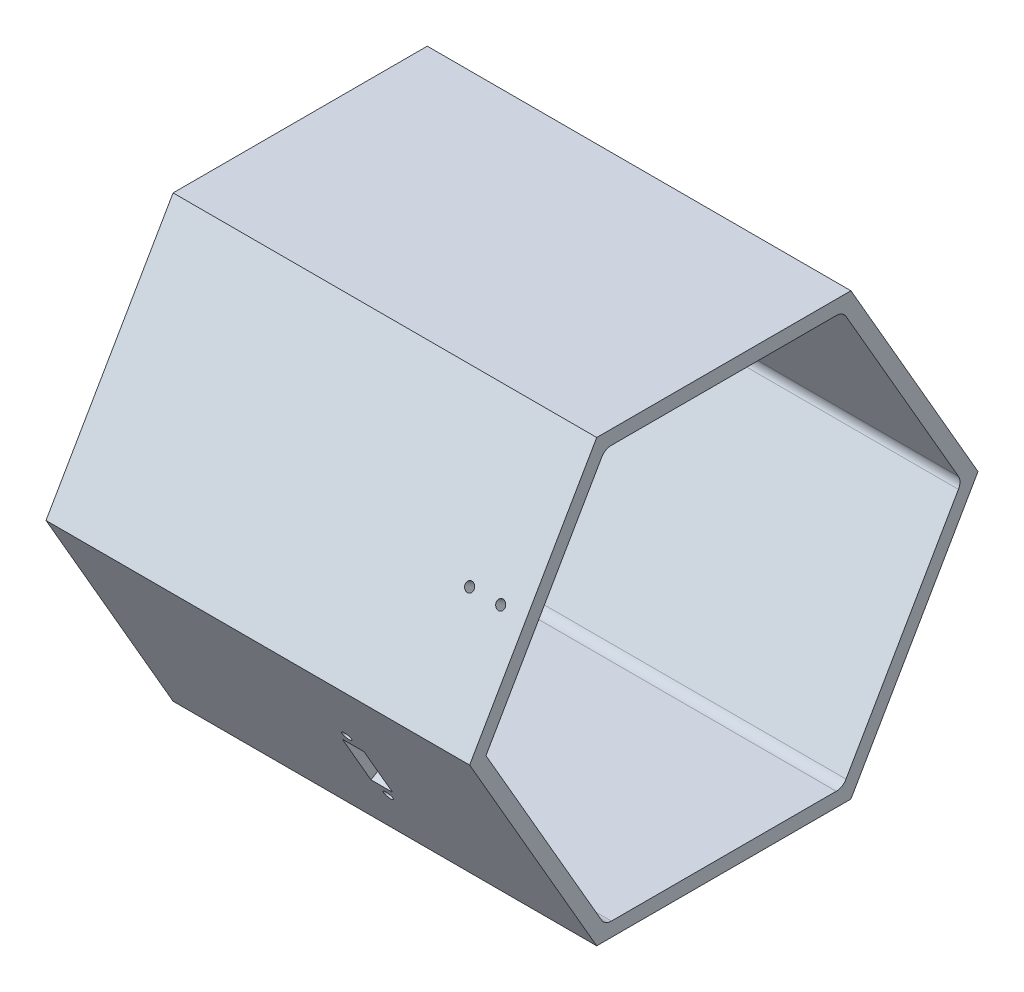
SolidWorks part; units mm, degrees
other "Markup1"
sketch "Sketch8"
ref_plane "Front Plane" through (0, 0, 0) normal (0, 0, 1) x (1, 0, 0)
ref_plane "Top Plane" through (0, 0, 0) normal (0, 1, 0) x (1, 0, 0)
ref_plane "Right Plane" through (0, 0, 0) normal (1, 0, 0) x (0, 0, -1)
sketch "Sketch1" plane through (0, 0, 0) normal (1, 0, 0) x (0, 0, -1)
  line L1 (90, 0) -> (45, 77.9423)
  line L2 (45, 77.9423) -> (-45, 77.9423)
  line L3 (-45, 77.9423) -> (-90, 0)
  line L4 (-90, 0) -> (-45, -77.9423)
  line L5 (-45, -77.9423) -> (45, -77.9423)
  line L6 (45, -77.9423) -> (90, 0)
  circle A0 centre (0, 0) radius 77.9423 construction
  dimension "D1" = 180
extrude "Boss-Extrude1" add sketch "Sketch1" along normal blind 200
sketch "Sketch2" plane through (200, 0, 0) normal (1, 0, 0) x (0, 0, -1)
  line L0 (-45, 77.9423) -> (-90, 0) construction
  line L1 (84.2265, 0) -> (42.1132, 72.9423)
  line L2 (42.1132, 72.9423) -> (-42.1132, 72.9423)
  line L3 (-42.1132, 72.9423) -> (-84.2265, 0)
  line L4 (-84.2265, 0) -> (-42.1132, -72.9423)
  line L5 (-42.1132, -72.9423) -> (42.1132, -72.9423)
  line L6 (42.1132, -72.9423) -> (84.2265, 0)
  circle A0 centre (0, 0) radius 72.9423 construction
  dimension "D1" = 5
extrude "Cut-Extrude1" cut sketch "Sketch2" against normal blind 195
sketch "Sketch5" plane through (0, -38.9711, 67.5) normal (0, -0.5, 0.866) x (1, 0, 0)
  line L0 (20, 45) -> (20, -45) construction
  line L1 (200, 45) -> (0, 45) construction
  line L2 (200, -45) -> (0, -45) construction
  line L3 (65, 45) -> (65, -45) construction
  line L4 (0, 45) -> (0, -45) construction
  line L5 (73.65, -5) -> (64, -5) construction
  line L6 (65, 5.1) -> (72.65, 5.1)
  line L7 (65, 5.1) -> (65, -15.1)
  line L8 (65, -15.1) -> (72.65, -15.1)
  line L9 (72.65, 5.1) -> (72.65, -15.1)
  line L10 (65, 5.1) -> (72.65, -15.1) construction
  line L11 (65, -15.1) -> (72.65, 5.1) construction
  line L12 (64, -15.5) -> (73.65, -15.5) construction
  line L13 (64, -15.5) -> (64, 5.5) construction
  line L14 (64, 5.5) -> (73.65, 5.5) construction
  line L15 (73.65, -15.5) -> (73.65, 5.5) construction
  line L16 (68.825, 14) -> (68.825, 5.5) construction
  line L17 (72.575, 9.75) -> (65.075, 9.75) construction
  line L18 (66.95, 6.5024) -> (70.7, 6.5024) construction
  line L19 (70.7, 6.5024) -> (72.575, 9.75) construction
  line L20 (72.575, 9.75) -> (70.7, 12.9976) construction
  line L21 (70.7, 12.9976) -> (66.95, 12.9976) construction
  line L22 (66.95, 12.9976) -> (65.075, 9.75) construction
  line L23 (65.075, 9.75) -> (66.95, 6.5024) construction
  arc A2 (73.65, 5.5) -> (64, 5.5) centre (68.825, 8.3806) ccw construction
  circle A3 centre (68.825, 9.75) radius 3.2476 construction
  circle A4 centre (68.825, 9.75) radius 1.65
  circle A6 centre (68.825, -19.75) radius 1.65
  point P14 (68.825, -5)
  point P15 (68.825, -5)
  dimension "D11" = 8.5
  dimension "D12" = 3.3
  dimension "D1" = 20
  dimension "D2" = 65
  dimension "D3" = 39.9
  dimension "D4" = 20.2
  dimension "D5" = 7.65
  dimension "D6" = 29.9
  dimension "D7" = 9.65
  dimension "D8" = 21
  dimension "D9" = 1
  dimension "D10" = 0.4
extrude "Cut-Extrude4" cut sketch "Sketch5" against normal blind 70
sketch "Sketch7" plane through (5, 0, 0) normal (1, 0, 0) x (0, 0, -1)
  line L0 (42.1132, 72.9423) -> (-42.1132, -72.9423) construction
  line L1 (-42.1132, 72.9423) -> (42.1132, -72.9423) construction
  line L2 (84.2265, 0) -> (-84.2265, 0) construction
  circle A0 centre (0, 0) radius 4.5
  circle A1 centre (60, 0) radius 3
  circle A2 centre (30, 51.9615) radius 3
  circle A3 centre (-30, 51.9615) radius 3
  circle A4 centre (-60, 0) radius 3
  circle A5 centre (-30, -51.9615) radius 3
  circle A6 centre (30, -51.9615) radius 3
  dimension "D1" = 9
  dimension "D2" = 6
  dimension "D3" = 6
  dimension "D4" = 6
  dimension "D5" = 6
  dimension "D6" = 6
  dimension "D7" = 6
  dimension "D8" = 60
  dimension "D9" = 60
  dimension "D10" = 60
  dimension "D11" = 60
  dimension "D12" = 60
  dimension "D13" = 60
extrude "Cut-Extrude6" cut sketch "Sketch7" against normal blind 70
fillet "Fillet1" radius 4 11 edges at (102.5, 0, -84.2265) (5, -72.9423, 0) (5, -36.4711, -63.1699) (102.5, -72.9423, -42.1132) (102.5, -72.9423, 42.1132) (5, -36.4711, 63.1699) (5, 36.4711, 63.1699) (102.5, 72.9423, 42.1132) (5, 72.9423, 0) (102.5, 72.9423, -42.1132) (5, 36.4711, -63.1699)
sketch "Sketch9" plane through (200, 0, 0) normal (1, 0, 0) x (0, 0, -1)
  line L0 (45, 77.9423) -> (90, 0)
  line L1 (90, 0) -> (45, -77.9423)
  line L2 (45, -77.9423) -> (-45, -77.9423)
  line L3 (-45, -77.9423) -> (-90, 0)
  line L4 (-90, 0) -> (-45, 77.9423)
  line L5 (-45, 77.9423) -> (45, 77.9423)
extrude "Cut-Extrude7" cut sketch "Sketch9" against normal blind 70
sketch "Sketch10" plane through (0, 38.9711, 67.5) normal (0, 0.5, 0.866) x (1, 0, 0)
  line L0 (130, 45) -> (130, -45) construction
  line L4 (130, 45) -> (0, 45) construction
  line L5 (150.288, -5) -> (110, -5) construction
  line L6 (130, -45) -> (0, -45) construction
  circle A0 centre (110, -5) radius 1.6
  circle A1 centre (121, -5) radius 1.6
  dimension "D1" = 3.2
  dimension "D4" = 3.2
  dimension "D2" = 20
  dimension "D3" = 50
  dimension "D5" = 11
extrude "Cut-Extrude8" cut sketch "Sketch10" against normal blind 6
sketch "Sketch11" plane through (0, 0, 0) normal (-1, 0, 0) x (0, 0, 1)
  line L0 (90, 0) -> (45, 77.9423)
  line L1 (45, 77.9423) -> (-45, 77.9423)
  line L2 (-45, 77.9423) -> (-90, 0)
  line L3 (-90, 0) -> (-45, -77.9423)
  line L4 (-45, -77.9423) -> (45, -77.9423)
  line L5 (45, -77.9423) -> (90, 0)
  line L7 (84.2265, 0) -> (42.1132, 72.9423)
  line L8 (42.1132, 72.9423) -> (-42.1132, 72.9423)
  line L9 (-42.1132, 72.9423) -> (-84.2265, 0)
  line L10 (-84.2265, 0) -> (-42.1132, -72.9423)
  line L11 (-42.1132, -72.9423) -> (42.1132, -72.9423)
  line L12 (42.1132, -72.9423) -> (84.2265, 0)
  circle A0 centre (0, 0) radius 72.9423 construction
  dimension "D1" = 5
extrude "Boss-Extrude2" add sketch "Sketch11" along normal blind 20
sketch "Sketch13" plane through (0, 38.9711, 67.5) normal (0, 0.5, 0.866) x (1, 0, 0)
  line L0 (130, 45) -> (-20, 45) construction
  line L1 (110.374, 45) -> (30.374, 45)
  line L2 (110.374, 45) -> (110.374, -45)
  line L3 (110.374, -45) -> (30.374, -45)
  line L4 (30.374, 45) -> (30.374, -45)
  line L5 (110.374, 45) -> (30.374, -45) construction
  line L6 (110.374, -45) -> (30.374, 45) construction
  line L7 (130, -45) -> (-20, -45) construction
  point P4 (70.374, 0)
  dimension "D1" = 90
  dimension "D2" = 80
sketch "Sketch15" plane through (0, 77.9423, 0) normal (0, 1, 0) x (1, 0, 0)
  line L0 (130, -45) -> (-20, -45) construction
  line L1 (130, 45) -> (55, 45) construction
  line L2 (130, 45) -> (130, -45) construction
  line L3 (130, -45) -> (55, -45) construction
  line L4 (55, 45) -> (55, -45) construction
  line L5 (130, 45) -> (55, -45) construction
  line L6 (130, -45) -> (55, 45) construction
  point P4 (92.5, 0)
  dimension "D1" = 75
